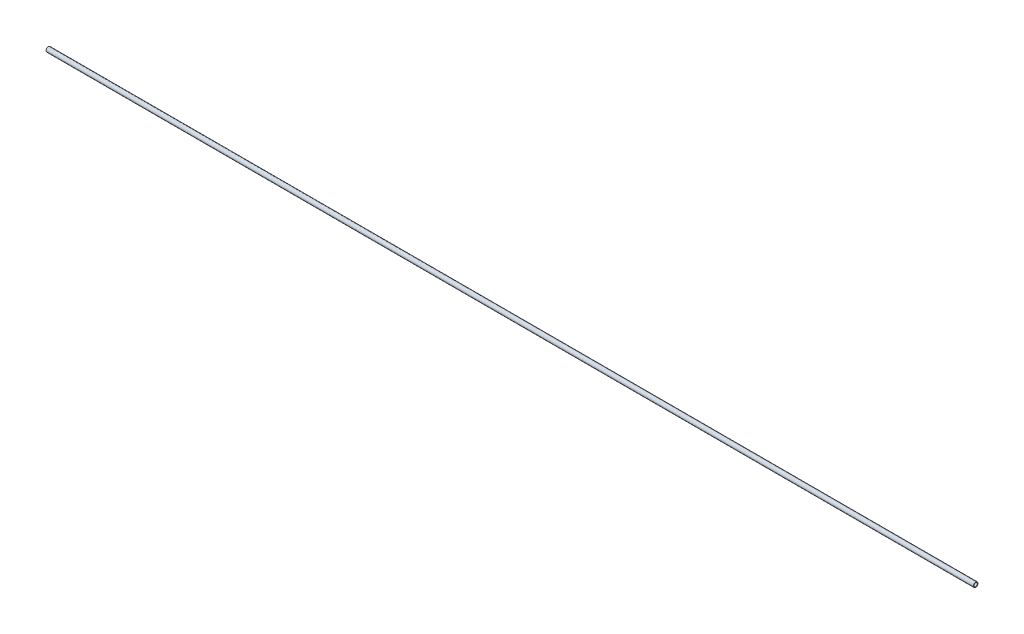
SolidWorks part; units mm, degrees
material "AISI 4130 Steel, annealed at 865C"
ref_plane "Front Plane" through (0, 0, 0) normal (0, 0, 1) x (1, 0, 0)
ref_plane "Top Plane" through (0, 0, 0) normal (0, 1, 0) x (1, 0, 0)
ref_plane "Right Plane" through (0, 0, 0) normal (1, 0, 0) x (0, 0, -1)
sketch "Sketch1" plane through (0, 0, 0) normal (1, 0, 0) x (0, 0, -1)
  circle A0 centre (0, 0) radius 12.7
  circle A1 centre (0, 0) radius 9.652
  dimension "D1" = 25.4
  dimension "D2" = 19.304
extrude "Boss-Extrude1" add sketch "Sketch1" along normal blind 5080
